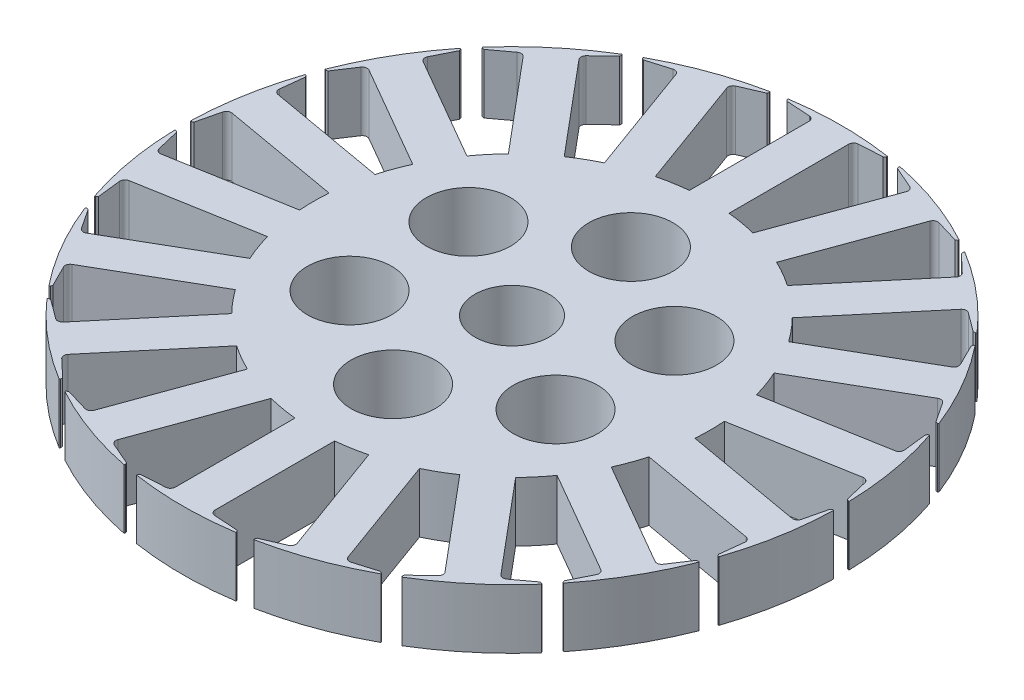
SolidWorks part; units mm, degrees
ref_plane "Front Plane" through (0, 0, 0) normal (0, 0, 1) x (1, 0, 0)
ref_plane "Top Plane" through (0, 0, 0) normal (0, 1, 0) x (1, 0, 0)
ref_plane "Right Plane" through (0, 0, 0) normal (1, 0, 0) x (0, 0, -1)
sketch "Sketch1" plane through (0, 0, 0) normal (0, 1, 0) x (1, 0, 0)
  line L0 (0, 0) -> (0, 66.5) construction
  line L1 (-9.7005, 65.22) -> (-10, 65.538)
  line L2 (10, 65.538) -> (10, 65.7438)
  line L3 (4, 39.7995) -> (4, 63.9352)
  line L4 (-4, 66.3796) -> (-4, 66.5)
  line L5 (-4.9399, 64.9334) -> (-9.7005, 65.22)
  line L6 (-10, 65.538) -> (-10, 65.7438)
  line L7 (10, 65.538) -> (10, 65.7438)
  line L8 (9.7005, 65.22) -> (10, 65.538)
  line L9 (-4, 39.7995) -> (-4, 63.9352)
  line L10 (4.9399, 64.9334) -> (9.7005, 65.22)
  line L11 (9.8535, 38.7674) -> (18.1084, 61.4475)
  line L12 (17.5665, 62.707) -> (13.191, 64.6045)
  line L13 (13.191, 64.6045) -> (13.0184, 65.0058)
  line L14 (13.0184, 65.0058) -> (13.0888, 65.1992)
  line L15 (17.371, 36.0312) -> (25.6259, 58.7114)
  line L16 (26.8505, 59.3279) -> (31.4221, 57.969)
  line L17 (31.4221, 57.969) -> (31.8123, 58.1654)
  line L18 (31.8123, 58.1654) -> (31.8826, 58.3588)
  line L19 (22.5184, 33.0593) -> (38.0326, 51.5484)
  line L20 (37.9542, 52.9172) -> (34.4916, 56.1968)
  line L21 (34.4916, 56.1968) -> (34.4666, 56.6329)
  line L22 (34.4666, 56.6329) -> (34.5989, 56.7906)
  line L23 (28.6468, 27.917) -> (44.1609, 46.4061)
  line L24 (45.5226, 46.5666) -> (49.3537, 43.726)
  line L25 (49.3537, 43.726) -> (49.7875, 43.7772)
  line L26 (49.7875, 43.7772) -> (49.9198, 43.9348)
  line L27 (32.4674, 23.3639) -> (53.3695, 35.4317)
  line L28 (53.764, 36.7448) -> (51.6319, 41.0109)
  line L29 (51.6319, 41.0109) -> (51.7576, 41.4293)
  line L30 (51.7576, 41.4293) -> (51.9358, 41.5322)
  line L31 (36.4674, 16.4356) -> (57.3695, 28.5035)
  line L32 (58.7039, 28.1886) -> (61.3324, 24.2091)
  line L33 (61.3324, 24.2091) -> (61.7576, 24.1088)
  line L34 (61.7576, 24.1088) -> (61.9358, 24.2117)
  line L35 (38.5003, 10.8503) -> (62.2693, 15.0415)
  line L36 (63.0891, 16.1404) -> (62.5447, 20.8785)
  line L37 (62.5447, 20.8785) -> (62.8059, 21.2286)
  line L38 (62.8059, 21.2286) -> (63.0085, 21.2644)
  line L39 (39.8894, 2.9719) -> (63.6585, 7.163)
  line L40 (64.8047, 6.4107) -> (65.9136, 1.7722)
  line L41 (65.9136, 1.7722) -> (66.2788, 1.5325)
  line L42 (66.2788, 1.5325) -> (66.4815, 1.5682)
  line L43 (39.8894, -2.9719) -> (63.6585, -7.163)
  line L44 (64.8047, -6.4107) -> (65.9136, -1.7722)
  line L45 (65.9136, -1.7722) -> (66.2788, -1.5325)
  line L46 (66.2788, -1.5325) -> (66.4815, -1.5682)
  line L47 (38.5003, -10.8503) -> (62.2693, -15.0415)
  line L48 (63.0891, -16.1404) -> (62.5447, -20.8785)
  line L49 (62.5447, -20.8785) -> (62.8059, -21.2286)
  line L50 (62.8059, -21.2286) -> (63.0085, -21.2644)
  line L51 (36.4674, -16.4356) -> (57.3695, -28.5035)
  line L52 (58.7039, -28.1886) -> (61.3324, -24.2091)
  line L53 (61.3324, -24.2091) -> (61.7576, -24.1088)
  line L54 (61.7576, -24.1088) -> (61.9358, -24.2117)
  line L55 (32.4674, -23.3639) -> (53.3695, -35.4317)
  line L56 (53.764, -36.7448) -> (51.6319, -41.0109)
  line L57 (51.6319, -41.0109) -> (51.7576, -41.4293)
  line L58 (51.7576, -41.4293) -> (51.9358, -41.5322)
  line L59 (28.6468, -27.917) -> (44.1609, -46.4061)
  line L60 (45.5226, -46.5666) -> (49.3537, -43.726)
  line L61 (49.3537, -43.726) -> (49.7875, -43.7772)
  line L62 (49.7875, -43.7772) -> (49.9198, -43.9348)
  line L63 (22.5184, -33.0593) -> (38.0326, -51.5484)
  line L64 (37.9542, -52.9172) -> (34.4916, -56.1968)
  line L65 (34.4916, -56.1968) -> (34.4666, -56.6329)
  line L66 (34.4666, -56.6329) -> (34.5989, -56.7906)
  line L67 (17.371, -36.0312) -> (25.6259, -58.7114)
  line L68 (26.8505, -59.3279) -> (31.4221, -57.969)
  line L69 (31.4221, -57.969) -> (31.8123, -58.1654)
  line L70 (31.8123, -58.1654) -> (31.8826, -58.3588)
  line L71 (9.8535, -38.7674) -> (18.1084, -61.4475)
  line L72 (17.5665, -62.707) -> (13.191, -64.6045)
  line L73 (13.191, -64.6045) -> (13.0184, -65.0058)
  line L74 (13.0184, -65.0058) -> (13.0888, -65.1992)
  line L75 (4, -39.7995) -> (4, -63.9352)
  line L76 (4.9399, -64.9334) -> (9.7005, -65.22)
  line L77 (9.7005, -65.22) -> (10, -65.538)
  line L78 (10, -65.538) -> (10, -65.7438)
  line L79 (-4, -39.7995) -> (-4, -63.9352)
  line L80 (-4.9399, -64.9334) -> (-9.7005, -65.22)
  line L81 (-9.7005, -65.22) -> (-10, -65.538)
  line L82 (-10, -65.538) -> (-10, -65.7438)
  line L83 (-9.8535, -38.7674) -> (-18.1084, -61.4475)
  line L84 (-17.5665, -62.707) -> (-13.191, -64.6045)
  line L85 (-13.191, -64.6045) -> (-13.0184, -65.0058)
  line L86 (-13.0184, -65.0058) -> (-13.0888, -65.1992)
  line L87 (-17.371, -36.0312) -> (-25.6259, -58.7114)
  line L88 (-26.8505, -59.3279) -> (-31.4221, -57.969)
  line L89 (-31.4221, -57.969) -> (-31.8123, -58.1654)
  line L90 (-31.8123, -58.1654) -> (-31.8826, -58.3588)
  line L91 (-22.5184, -33.0593) -> (-38.0326, -51.5484)
  line L92 (-37.9542, -52.9172) -> (-34.4916, -56.1968)
  line L93 (-34.4916, -56.1968) -> (-34.4666, -56.6329)
  line L94 (-34.4666, -56.6329) -> (-34.5989, -56.7906)
  line L95 (-28.6468, -27.917) -> (-44.1609, -46.4061)
  line L96 (-45.5226, -46.5666) -> (-49.3537, -43.726)
  line L97 (-49.3537, -43.726) -> (-49.7875, -43.7772)
  line L98 (-49.7875, -43.7772) -> (-49.9198, -43.9348)
  line L99 (-32.4674, -23.3639) -> (-53.3695, -35.4317)
  line L100 (-53.764, -36.7448) -> (-51.6319, -41.0109)
  line L101 (-51.6319, -41.0109) -> (-51.7576, -41.4293)
  line L102 (-51.7576, -41.4293) -> (-51.9358, -41.5322)
  line L103 (-36.4674, -16.4356) -> (-57.3695, -28.5035)
  line L104 (-58.7039, -28.1886) -> (-61.3324, -24.2091)
  line L105 (-61.3324, -24.2091) -> (-61.7576, -24.1088)
  line L106 (-61.7576, -24.1088) -> (-61.9358, -24.2117)
  line L107 (-38.5003, -10.8503) -> (-62.2693, -15.0415)
  line L108 (-63.0891, -16.1404) -> (-62.5447, -20.8785)
  line L109 (-62.5447, -20.8785) -> (-62.8059, -21.2286)
  line L110 (-62.8059, -21.2286) -> (-63.0085, -21.2644)
  line L111 (-39.8894, -2.9719) -> (-63.6585, -7.163)
  line L112 (-64.8047, -6.4107) -> (-65.9136, -1.7722)
  line L113 (-65.9136, -1.7722) -> (-66.2788, -1.5325)
  line L114 (-66.2788, -1.5325) -> (-66.4815, -1.5682)
  line L115 (-39.8894, 2.9719) -> (-63.6585, 7.163)
  line L116 (-64.8047, 6.4107) -> (-65.9136, 1.7722)
  line L117 (-65.9136, 1.7722) -> (-66.2788, 1.5325)
  line L118 (-66.2788, 1.5325) -> (-66.4815, 1.5682)
  line L119 (-38.5003, 10.8503) -> (-62.2693, 15.0415)
  line L120 (-63.0891, 16.1404) -> (-62.5447, 20.8785)
  line L121 (-62.5447, 20.8785) -> (-62.8059, 21.2286)
  line L122 (-62.8059, 21.2286) -> (-63.0085, 21.2644)
  line L123 (-36.4674, 16.4356) -> (-57.3695, 28.5035)
  line L124 (-58.7039, 28.1886) -> (-61.3324, 24.2091)
  line L125 (-61.3324, 24.2091) -> (-61.7576, 24.1088)
  line L126 (-61.7576, 24.1088) -> (-61.9358, 24.2117)
  line L127 (-32.4674, 23.3639) -> (-53.3695, 35.4317)
  line L128 (-53.764, 36.7448) -> (-51.6319, 41.0109)
  line L129 (-51.6319, 41.0109) -> (-51.7576, 41.4293)
  line L130 (-51.7576, 41.4293) -> (-51.9358, 41.5322)
  line L131 (-28.6468, 27.917) -> (-44.1609, 46.4061)
  line L132 (-45.5226, 46.5666) -> (-49.3537, 43.726)
  line L133 (-49.3537, 43.726) -> (-49.7875, 43.7772)
  line L134 (-49.7875, 43.7772) -> (-49.9198, 43.9348)
  line L135 (-22.5184, 33.0593) -> (-38.0326, 51.5484)
  line L136 (-37.9542, 52.9172) -> (-34.4916, 56.1968)
  line L137 (-34.4916, 56.1968) -> (-34.4666, 56.6329)
  line L138 (-34.4666, 56.6329) -> (-34.5989, 56.7906)
  line L139 (-17.371, 36.0312) -> (-25.6259, 58.7114)
  line L140 (-26.8505, 59.3279) -> (-31.4221, 57.969)
  line L141 (-31.4221, 57.969) -> (-31.8123, 58.1654)
  line L142 (-31.8123, 58.1654) -> (-31.8826, 58.3588)
  line L143 (-9.8535, 38.7674) -> (-18.1084, 61.4475)
  line L144 (-17.5665, 62.707) -> (-13.191, 64.6045)
  line L145 (-13.191, 64.6045) -> (-13.0184, 65.0058)
  line L146 (-13.0184, 65.0058) -> (-13.0888, 65.1992)
  arc A0 (-34.5989, 56.7906) -> (-49.9198, 43.9348) centre (0, 0) ccw
  arc A1 (-28.6468, 27.917) -> (-32.4674, 23.3639) centre (0, 0) ccw
  circle A2 centre (0, 0) radius 7.5
  circle A3 centre (0, 24) radius 8.5
  circle A4 centre (20.7846, 12) radius 8.5
  circle A5 centre (20.7846, -12) radius 8.5
  circle A6 centre (0, -24) radius 8.5
  circle A7 centre (-20.7846, -12) radius 8.5
  circle A8 centre (-20.7846, 12) radius 8.5
  arc A11 (-4.9399, 64.9334) -> (-4, 63.9352) centre (-5, 63.9352) cw
  arc A12 (4.9399, 64.9334) -> (4, 63.9352) centre (5, 63.9352) ccw
  arc A13 (17.5665, 62.707) -> (18.1084, 61.4475) centre (17.1687, 61.7895) cw
  arc A14 (26.8505, 59.3279) -> (25.6259, 58.7114) centre (26.5656, 58.3693) ccw
  arc A15 (37.9542, 52.9172) -> (38.0326, 51.5484) centre (37.2665, 52.1911) cw
  arc A16 (45.5226, 46.5666) -> (44.1609, 46.4061) centre (44.927, 45.7633) ccw
  arc A17 (53.764, 36.7448) -> (53.3695, 35.4317) centre (52.8695, 36.2977) cw
  arc A18 (58.7039, 28.1886) -> (57.3695, 28.5035) centre (57.8695, 27.6375) ccw
  arc A19 (63.0891, 16.1404) -> (62.2693, 15.0415) centre (62.0956, 16.0263) cw
  arc A20 (64.8047, 6.4107) -> (63.6585, 7.163) centre (63.8321, 6.1782) ccw
  arc A21 (64.8047, -6.4107) -> (63.6585, -7.163) centre (63.8321, -6.1782) cw
  arc A22 (63.0891, -16.1404) -> (62.2693, -15.0415) centre (62.0956, -16.0263) ccw
  arc A23 (58.7039, -28.1886) -> (57.3695, -28.5035) centre (57.8695, -27.6375) cw
  arc A24 (53.764, -36.7448) -> (53.3695, -35.4317) centre (52.8695, -36.2977) ccw
  arc A25 (45.5226, -46.5666) -> (44.1609, -46.4061) centre (44.927, -45.7633) cw
  arc A26 (37.9542, -52.9172) -> (38.0326, -51.5484) centre (37.2665, -52.1911) ccw
  arc A27 (26.8505, -59.3279) -> (25.6259, -58.7114) centre (26.5656, -58.3693) cw
  arc A28 (17.5665, -62.707) -> (18.1084, -61.4475) centre (17.1687, -61.7895) ccw
  arc A29 (4.9399, -64.9334) -> (4, -63.9352) centre (5, -63.9352) cw
  arc A30 (-4.9399, -64.9334) -> (-4, -63.9352) centre (-5, -63.9352) ccw
  arc A31 (-17.5665, -62.707) -> (-18.1084, -61.4475) centre (-17.1687, -61.7895) cw
  arc A32 (-26.8505, -59.3279) -> (-25.6259, -58.7114) centre (-26.5656, -58.3693) ccw
  arc A33 (-37.9542, -52.9172) -> (-38.0326, -51.5484) centre (-37.2665, -52.1911) cw
  arc A34 (-45.5226, -46.5666) -> (-44.1609, -46.4061) centre (-44.927, -45.7633) ccw
  arc A35 (-53.764, -36.7448) -> (-53.3695, -35.4317) centre (-52.8695, -36.2977) cw
  arc A36 (-58.7039, -28.1886) -> (-57.3695, -28.5035) centre (-57.8695, -27.6375) ccw
  arc A37 (-63.0891, -16.1404) -> (-62.2693, -15.0415) centre (-62.0956, -16.0263) cw
  arc A38 (-64.8047, -6.4107) -> (-63.6585, -7.163) centre (-63.8321, -6.1782) ccw
  arc A39 (-64.8047, 6.4107) -> (-63.6585, 7.163) centre (-63.8321, 6.1782) cw
  arc A40 (-63.0891, 16.1404) -> (-62.2693, 15.0415) centre (-62.0956, 16.0263) ccw
  arc A41 (-58.7039, 28.1886) -> (-57.3695, 28.5035) centre (-57.8695, 27.6375) cw
  arc A42 (-53.764, 36.7448) -> (-53.3695, 35.4317) centre (-52.8695, 36.2977) ccw
  arc A43 (-45.5226, 46.5666) -> (-44.1609, 46.4061) centre (-44.927, 45.7633) cw
  arc A44 (-37.9542, 52.9172) -> (-38.0326, 51.5484) centre (-37.2665, 52.1911) ccw
  arc A45 (-26.8505, 59.3279) -> (-25.6259, 58.7114) centre (-26.5656, 58.3693) cw
  arc A46 (-17.5665, 62.707) -> (-18.1084, 61.4475) centre (-17.1687, 61.7895) ccw
  arc A47 (-51.9358, 41.5322) -> (-61.9358, 24.2117) centre (0, 0) ccw
  arc A48 (-63.0085, 21.2644) -> (-66.4815, 1.5682) centre (0, 0) ccw
  arc A49 (-66.4815, -1.5682) -> (-63.0085, -21.2644) centre (0, 0) ccw
  arc A50 (-61.9358, -24.2117) -> (-51.9358, -41.5322) centre (0, 0) ccw
  arc A51 (-49.9198, -43.9348) -> (-34.5989, -56.7906) centre (0, 0) ccw
  arc A52 (-31.8826, -58.3588) -> (-13.0888, -65.1992) centre (0, 0) ccw
  arc A53 (-10, -65.7438) -> (10, -65.7438) centre (0, 0) ccw
  arc A54 (13.0888, -65.1992) -> (31.8826, -58.3588) centre (0, 0) ccw
  arc A55 (34.5989, -56.7906) -> (49.9198, -43.9348) centre (0, 0) ccw
  arc A56 (51.9358, -41.5322) -> (61.9358, -24.2117) centre (0, 0) ccw
  arc A57 (63.0085, -21.2644) -> (66.4815, -1.5682) centre (0, 0) ccw
  arc A58 (66.4815, 1.5682) -> (63.0085, 21.2644) centre (0, 0) ccw
  arc A59 (61.9358, 24.2117) -> (51.9358, 41.5322) centre (0, 0) ccw
  arc A60 (49.9198, 43.9348) -> (34.5989, 56.7906) centre (0, 0) ccw
  arc A61 (31.8826, 58.3588) -> (13.0888, 65.1992) centre (0, 0) ccw
  arc A62 (10, 65.7438) -> (-10, 65.7438) centre (0, 0) ccw
  arc A63 (-13.0888, 65.1992) -> (-31.8826, 58.3588) centre (0, 0) ccw
  arc A64 (-17.371, 36.0312) -> (-22.5184, 33.0593) centre (0, 0) ccw
  arc A65 (-4, 39.7995) -> (-9.8535, 38.7674) centre (0, 0) ccw
  arc A66 (9.8535, 38.7674) -> (4, 39.7995) centre (0, 0) ccw
  arc A67 (-36.4674, 16.4356) -> (-38.5003, 10.8503) centre (0, 0) ccw
  arc A68 (-39.8894, 2.9719) -> (-39.8894, -2.9719) centre (0, 0) ccw
  arc A69 (-38.5003, -10.8503) -> (-36.4674, -16.4356) centre (0, 0) ccw
  arc A70 (-32.4674, -23.3639) -> (-28.6468, -27.917) centre (0, 0) ccw
  arc A71 (-22.5184, -33.0593) -> (-17.371, -36.0312) centre (0, 0) ccw
  arc A72 (-9.8535, -38.7674) -> (-4, -39.7995) centre (0, 0) ccw
  arc A73 (4, -39.7995) -> (9.8535, -38.7674) centre (0, 0) ccw
  arc A74 (17.371, -36.0312) -> (22.5184, -33.0593) centre (0, 0) ccw
  arc A75 (28.6468, -27.917) -> (32.4674, -23.3639) centre (0, 0) ccw
  arc A76 (36.4674, -16.4356) -> (38.5003, -10.8503) centre (0, 0) ccw
  arc A77 (39.8894, -2.9719) -> (39.8894, 2.9719) centre (0, 0) ccw
  arc A78 (38.5003, 10.8503) -> (36.4674, 16.4356) centre (0, 0) ccw
  arc A79 (32.4674, 23.3639) -> (28.6468, 27.917) centre (0, 0) ccw
  arc A80 (22.5184, 33.0593) -> (17.371, 36.0312) centre (0, 0) ccw
  point P19 (0, 0)
  point P21 (4, 0)
  point P22 (4, 66.5)
  point P23 (-4, 0)
  point P25 (10, 0)
  point P26 (10, 66.5)
  point P27 (-10, 0)
  point P28 (-10, 66.5)
  point P30 (-10, 65.238)
  point P284 (0, 0)
  dimension "D1" = 15
  dimension "D2" = 80
  dimension "D3" = 133
  dimension "D5" = 17
  dimension "D7" = 18
  dimension "D9" = 1
  dimension "D4" = 24
  dimension "D10" = 8
  dimension "D6" = 6
extrude "Boss-Extrude1" add sketch "Sketch1" along normal blind 12
